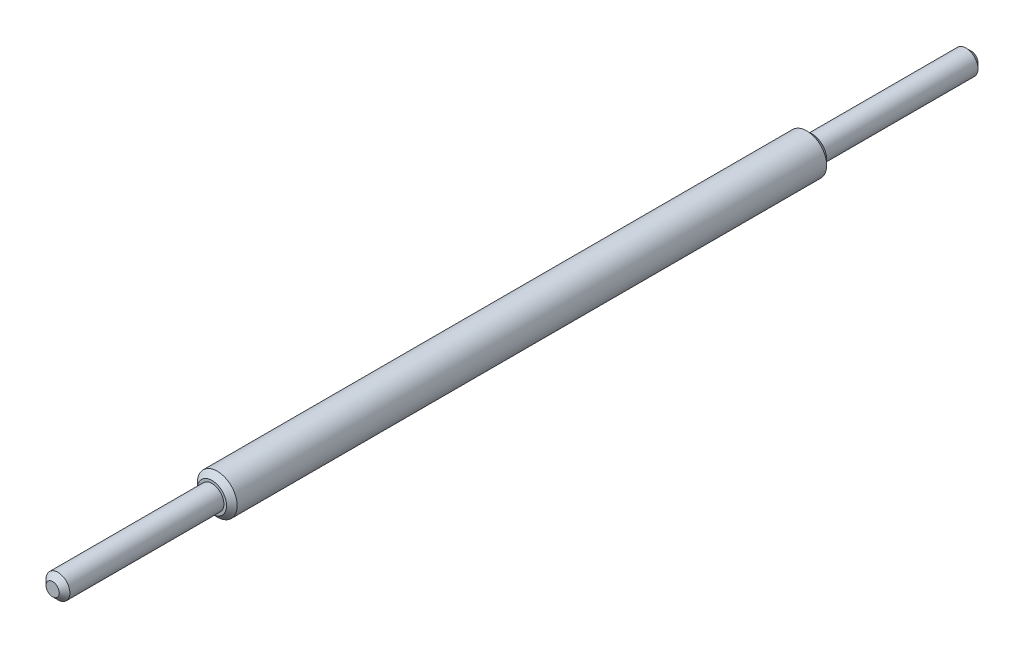
SolidWorks part; units mm, degrees
ref_plane "前视基准面" through (0, 0, 0) normal (0, 0, 1) x (1, 0, 0)
ref_plane "上视基准面" through (0, 0, 0) normal (0, 1, 0) x (1, 0, 0)
ref_plane "右视基准面" through (0, 0, 0) normal (1, 0, 0) x (0, 0, -1)
sketch "草图1" plane through (0, 0, 0) normal (0, 0, 1) x (1, 0, 0)
  circle A0 centre (0, 0) radius 4.5
  dimension "D1" = 9
extrude "凸台-拉伸1" add sketch "草图1" along normal mid plane 346
sketch "草图2" plane through (0, 0, 173) normal (0, 0, 1) x (1, 0, 0)
  circle A0 centre (0, 0) radius 7.5
  dimension "D1" = 15
extrude "凸台-拉伸2" add sketch "草图2" against normal offset from surface (226 mm away) 60 from offset 60 up to face at (4.5, 0, -173) offset against normal yes
chamfer "倒角1" distance 2 angle 45 4 edges at (4.5, 0, -173) (4.5, 0, 173) (7.5, 0, -113) (7.5, 0, 113)
